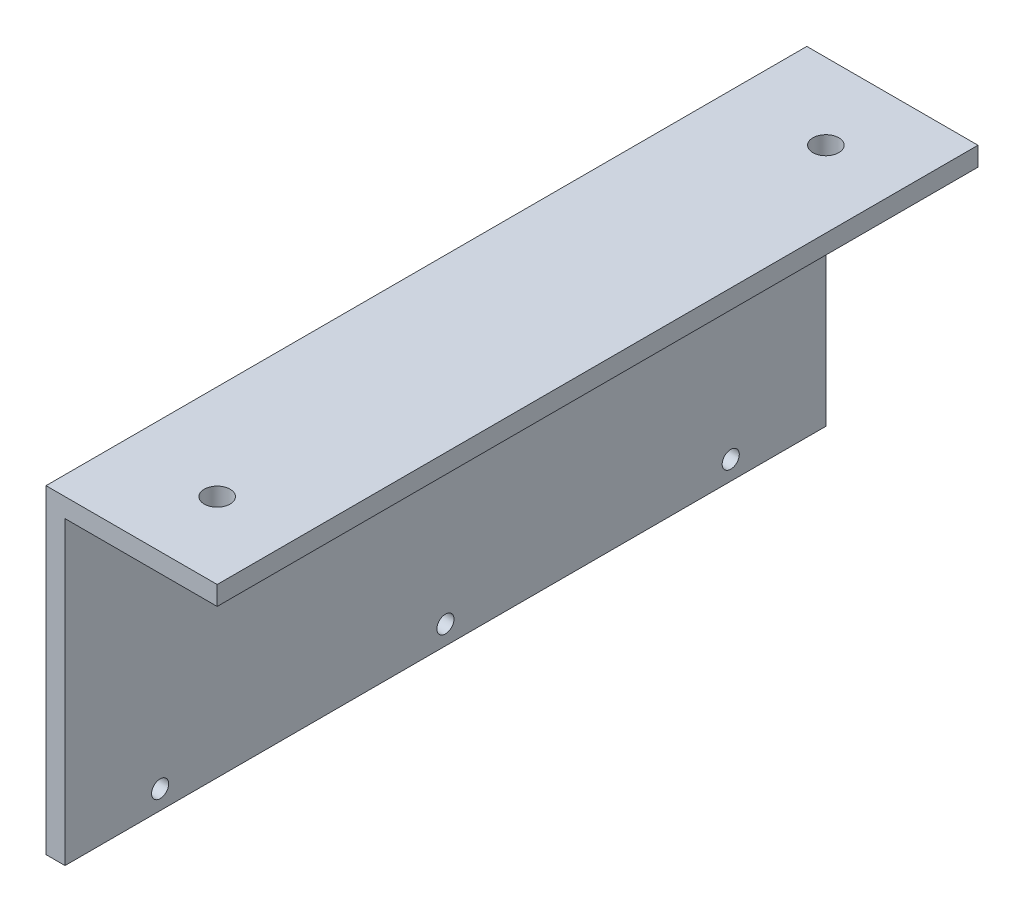
SolidWorks part; units mm, degrees
ref_plane "Plan de face" through (0, 0, 0) normal (0, 0, 1) x (1, 0, 0)
ref_plane "Plan de dessus" through (0, 0, 0) normal (0, 1, 0) x (1, 0, 0)
ref_plane "Plan de droite" through (0, 0, 0) normal (1, 0, 0) x (0, 0, -1)
sketch "Esquisse1" plane through (0, 0, 0) normal (0, 0, 1) x (1, 0, 0)
  line L0 (0, 0) -> (0, 84)
  line L1 (0, 84) -> (45, 84)
  line L2 (5, 0) -> (5, 79)
  line L3 (5, 79) -> (45, 79)
  line L4 (0, 0) -> (5, 0)
  line L5 (45, 79) -> (45, 84)
  dimension "D1" = 84
  dimension "D2" = 45
  dimension "D3" = 5
extrude "Boss.-Extru.1" add sketch "Esquisse1" along normal blind 200
hole_wizard "Trou taraudé M81" positions "Esquisse3" profile "Esquisse2" tap size "M8" standard "ISO" end condition through all
sketch "Esquisse3" plane through (0, 79, 0) normal (0, -1, 0) x (-1, 0, 0)
  line L0 (-25, -180) -> (-25, -20) construction
  line L2 (18.6337, -100) -> (-92.5283, -100) construction
  line L4 (-5, -200) -> (-45, -200) construction
  line L5 (-5, 0) -> (-45, 0) construction
  line L6 (-5, -200) -> (-5, 0) construction
  point P0 (-25, -180)
  point P2 (-25, -20)
  dimension "D1" = 20
  dimension "D2" = 160
sketch "Esquisse2" plane through (25, 79, 180) normal (1, 0, 0) x (0, 0, -1)
  line L0 (0, 0) -> (0, 5)
  line L1 (0, 5) -> (3.4, 5)
  line L2 (3.4, 5) -> (3.4, 0)
  line L5 (3.4, 0) -> (0, 0)
  line L11 (0, -6.35) -> (0, 107.95) construction
  dimension "Diamètre du trou pour taraudage jusqu'au prochain" = 6.8
  dimension "Profondeur du trou pour taraudage jusqu'au prochain" = 5
cosmetic thread "Filetage de perçage1" parameters "D2"=8
cosmetic thread "Filetage de perçage2" parameters "D2"=8
hole_wizard "Dégagement M41" positions "Esquisse5" profile "Esquisse4" hole size "M4" standard "ISO" end condition through all
sketch "Esquisse5" plane through (0, 0, 0) normal (-1, 0, 0) x (0, 0, 1)
  line L0 (25, 5) -> (175, 5) construction
  line L2 (200, 0) -> (0, 0) construction
  line L3 (100, 57.7726) -> (100, -31.0363) construction
  line L5 (0, 84) -> (0, 0) construction
  line L6 (200, 84) -> (200, 0) construction
  point P0 (175, 5)
  point P3 (100, 5)
  point P6 (25, 5)
  dimension "D1" = 5
  dimension "D2" = 150
sketch "Esquisse4" plane through (0, 5, 175) normal (0, 1, 0) x (0, 0, 1)
  line L0 (0, 0) -> (0, 45)
  line L1 (0, 45) -> (2.25, 45)
  line L2 (2.25, 45) -> (2.25, 0)
  line L5 (2.25, 0) -> (0, 0)
  line L11 (0, -6.35) -> (0, 107.95) construction
  dimension "Diamètre du perçage jusqu'au prochain" = 4.5
  dimension "Profondeur du perçage jusqu'au prochain" = 45
